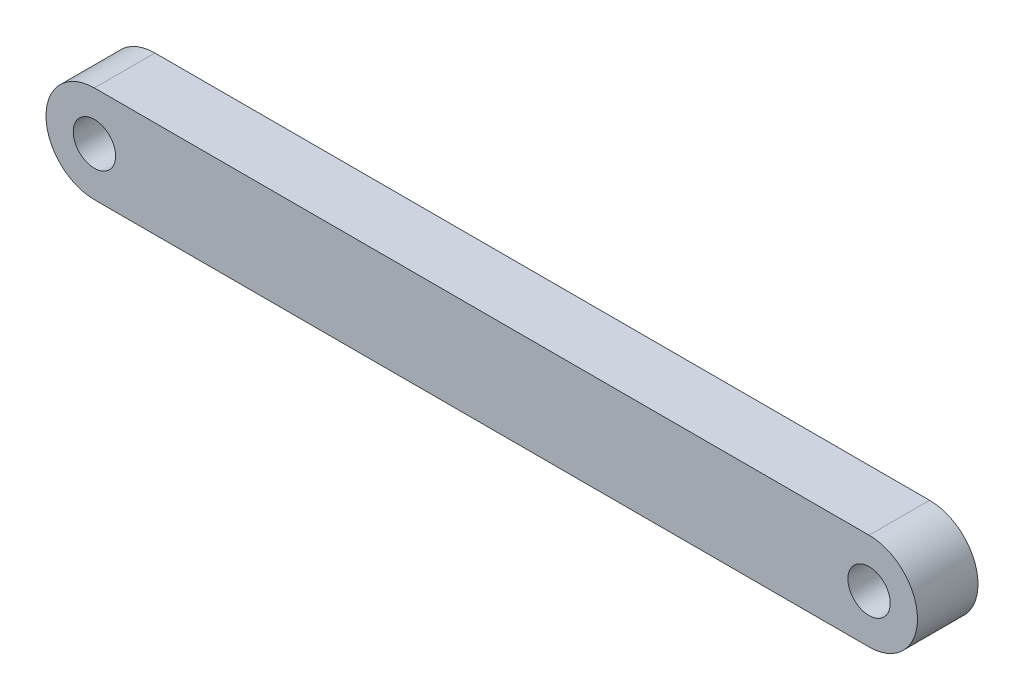
SolidWorks part; units mm, degrees
ref_plane "Front Plane" through (0, 0, 0) normal (1, 0, 0) x (0, 1, 0)
ref_plane "Top Plane" through (0, 0, 0) normal (0, 0, 1) x (0, 1, 0)
ref_plane "Right Plane" through (0, 0, 0) normal (0, 1, 0) x (-1, 0, 0)
sketch "Sketch1" plane through (0, 0, 0) normal (0, 0, 1) x (0, 1, 0)
  line L0 (0, 0) -> (0, 64) construction
  line L1 (-4, 0) -> (-4, 64)
  line L2 (4, 0) -> (4, 64)
  arc A0 (-4, 0) -> (4, 0) centre (0, 0) ccw
  arc A1 (4, 64) -> (-4, 64) centre (0, 64) ccw
  circle A2 centre (0, 64) radius 1.75
  circle A3 centre (0, 0) radius 1.75
  point P3 (0, 32)
  dimension "D2" = 4
  dimension "D3" = 3.5
  dimension "D1" = 64
extrude "Boss-Extrude1" add sketch "Sketch1" along normal blind 5
